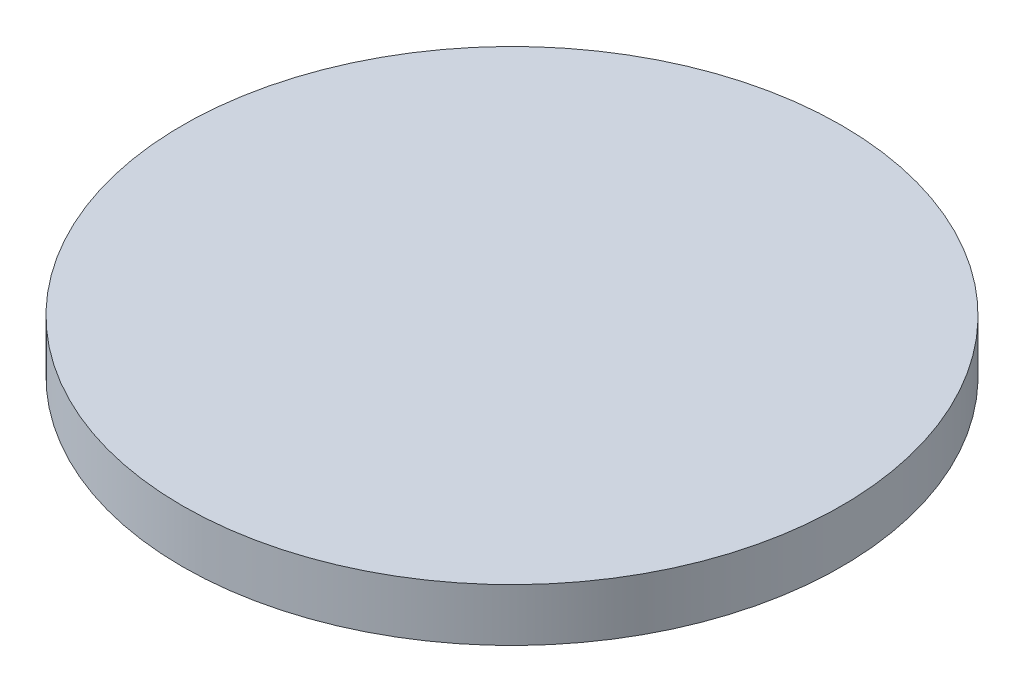
SolidWorks part; units mm, degrees
material "Glass"
ref_plane "Front Plane" through (0, 0, 0) normal (0, 0, 1) x (1, 0, 0)
ref_plane "Top Plane" through (0, 0, 0) normal (0, 1, 0) x (1, 0, 0)
ref_plane "Right Plane" through (0, 0, 0) normal (1, 0, 0) x (0, 0, -1)
sketch "Sketch1" plane through (0, 0, 0) normal (0, 1, 0) x (1, 0, 0)
  circle A0 centre (0, 0) radius 12.5
  dimension "D1" = 25
extrude "Boss-Extrude1" add sketch "Sketch1" along normal blind 2
